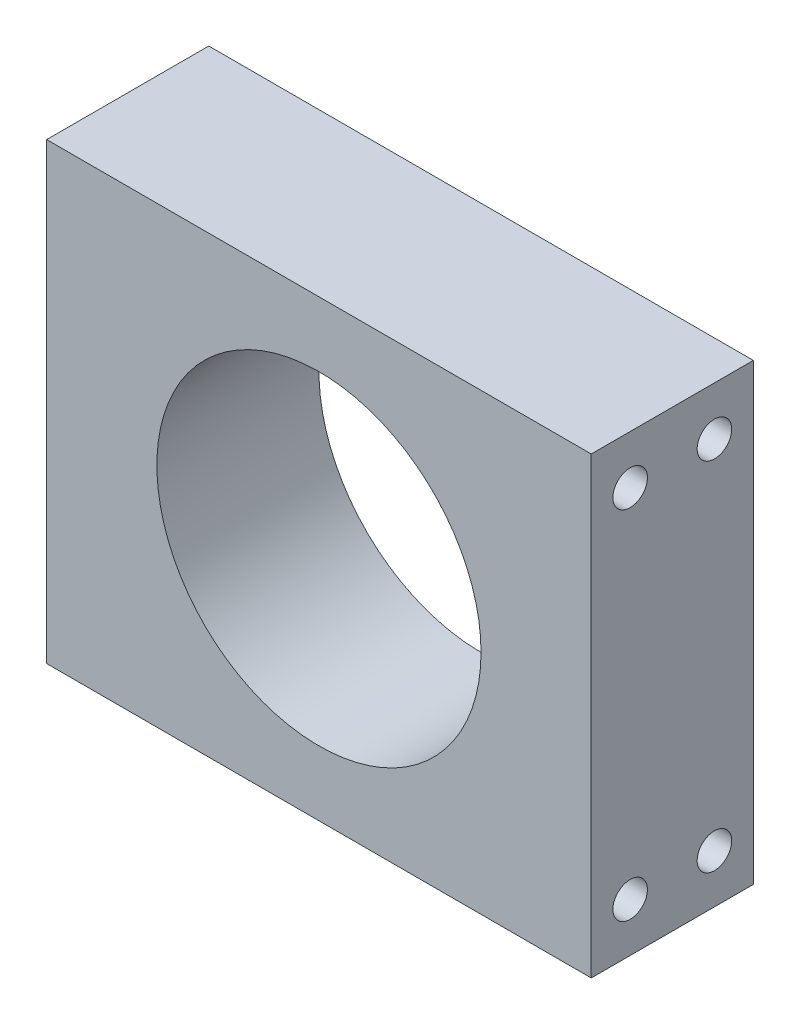
SolidWorks part; units mm, degrees
ref_plane "Front Plane" through (0, 0, 0) normal (0, 0, 1) x (1, 0, 0)
ref_plane "Top Plane" through (0, 0, 0) normal (0, 1, 0) x (1, 0, 0)
ref_plane "Right Plane" through (0, 0, 0) normal (1, 0, 0) x (0, 0, -1)
sketch "Sketch2" plane through (0, 0, 0) normal (0, 0, 1) x (1, 0, 0)
  line L1 (21.336, -17.78) -> (-21.336, -17.78)
  line L2 (21.336, -17.78) -> (21.336, 17.78)
  line L3 (21.336, 17.78) -> (-21.336, 17.78)
  line L4 (-21.336, -17.78) -> (-21.336, 17.78)
  line L5 (21.336, -17.78) -> (-21.336, 17.78) construction
  line L6 (21.336, 17.78) -> (-21.336, -17.78) construction
  circle A0 centre (0, 0) radius 12.7
  point P0 (0, 0)
  dimension "D1" = 25.4
  dimension "D2" = 35.56
  dimension "D3" = 42.672
extrude "Boss-Extrude1" add sketch "Sketch2" along normal blind 12.7
hole_wizard "Tap Drill for #6-32 Tap1" positions "Sketch3" profile "Sketch4" hole size "#6-32" standard "ANSI Inch"
sketch "Sketch3" plane through (21.336, 0, 0) normal (1, 0, 0) x (0, 0, -1)
  line L0 (0, -17.78) -> (0, 17.78) construction
  line L1 (-12.7, -17.78) -> (-12.7, 17.78) construction
  line L2 (-9.652, 13.97) -> (-3.048, 13.97)
  line L4 (-9.652, -13.97) -> (-3.048, -13.97)
  line L6 (-12.7, 17.78) -> (0, 17.78) construction
  line L7 (-12.7, -17.78) -> (0, -17.78) construction
  point P0 (-3.048, 13.97)
  point P2 (-3.048, -13.97)
  point P4 (-9.652, 13.97)
  point P6 (-9.652, -13.97)
  dimension "D1" = 3.048
  dimension "D2" = 3.048
  dimension "D3" = 3.048
  dimension "D4" = 3.048
  dimension "D5" = 3.81
  dimension "D6" = 3.81
sketch "Sketch4" plane through (21.336, 13.97, 3.048) normal (0, 1, 0) x (0, 0, -1)
  line L0 (0, 0) -> (0, 7.1627)
  line L1 (0, 7.1627) -> (1.3525, 6.35)
  line L2 (1.3525, 6.35) -> (1.3525, 0)
  line L5 (1.3525, 0) -> (0, 0)
  line L10 (0, 7.1627) -> (-1.3526, 6.35) construction
  line L11 (0, -6.35) -> (0, 107.95) construction
  dimension "Hole Dia." = 2.7051
  dimension "Hole Depth" = 6.35
  dimension "Drill Angle" = 118
mirror "Mirror1" about plane through (0, 0, 0) normal (1, 0, 0) of "Tap Drill for #6-32 Tap1"
